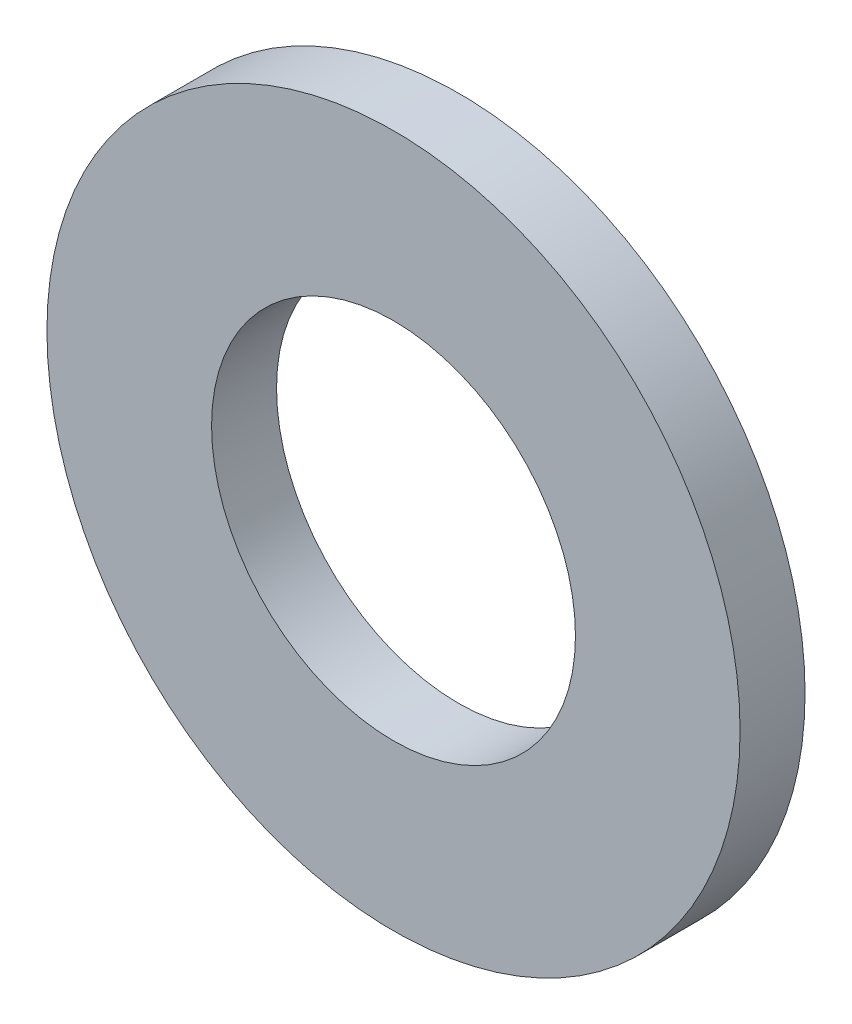
SolidWorks part; units mm, degrees
ref_plane "Plan de face" through (0, 0, 0) normal (0, 0, 1) x (1, 0, 0)
ref_plane "Plan de dessus" through (0, 0, 0) normal (0, 1, 0) x (1, 0, 0)
ref_plane "Plan de droite" through (0, 0, 0) normal (1, 0, 0) x (0, 0, -1)
sketch "Esquisse1" plane through (0, 0, 0) normal (0, 0, 1) x (1, 0, 0)
  circle A0 centre (0, 0) radius 8
  dimension "D1" = 16
extrude "Boss.-Extru.1" add sketch "Esquisse1" along normal blind 1.5
sketch "Esquisse2" plane through (0, 0, 1.5) normal (0, 0, 1) x (1, 0, 0)
  circle A0 centre (0, 0) radius 4.2
  dimension "D1" = 8.4
extrude "Enlèv. mat.-Extru.1" cut sketch "Esquisse2" against normal blind 1.5
